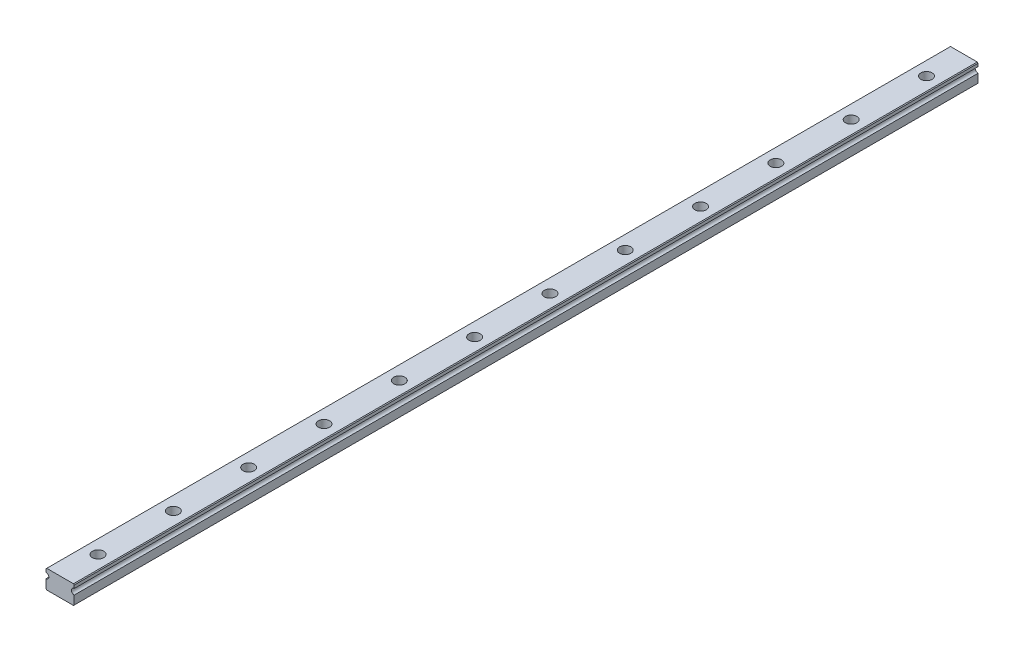
SolidWorks part; units mm, degrees
ref_plane "前视基准面" through (0, 0, 0) normal (0, 0, 1) x (1, 0, 0)
ref_plane "上视基准面" through (0, 0, 0) normal (0, 1, 0) x (1, 0, 0)
ref_plane "右视基准面" through (0, 0, 0) normal (1, 0, 0) x (0, 0, -1)
other "Configuration Table"
sketch "草图1" plane through (0, 0, 0) normal (0, 0, 1) x (1, 0, 0)
  line L0 (-7.6432, 0.2342) -> (-7.6432, -4.3658)
  line L1 (-7.6432, -4.3658) -> (-7.2432, -4.7658)
  line L2 (-7.2432, -4.7658) -> (6.9568, -4.7658)
  line L3 (6.9568, -4.7658) -> (7.3568, -4.3658)
  line L4 (7.3568, -4.3658) -> (7.3568, 0.2342)
  line L5 (7.3568, 3.2342) -> (7.3568, 4.8342)
  line L6 (7.3568, 4.8342) -> (6.9568, 5.2342)
  line L7 (6.9568, 5.2342) -> (-7.2432, 5.2342)
  line L8 (-7.2432, 5.2342) -> (-7.6432, 4.8342)
  line L9 (-7.6432, 4.8342) -> (-7.6432, 3.2342)
  arc A0 (5.8568, 1.7342) -> (7.3568, 0.2342) centre (7.3568, 1.7342) ccw
  arc A1 (7.3568, 3.2342) -> (5.8568, 1.7342) centre (7.3568, 1.7342) ccw
  arc A2 (-7.6432, 0.2342) -> (-7.6432, 3.2342) centre (-7.6432, 1.7342) ccw
extrude "凸台-拉伸1" add sketch "草图1" along normal blind 1000
sketch "草图2" plane through (0, 5.2342, 0) normal (0, 1, 0) x (1, 0, 0)
  line L0 (6.9568, 0) -> (-7.2432, 0) construction
  circle A0 centre (0, -20) radius 1.5
  dimension "D1" = 3
  dimension "D2" = 20
extrude "切除-拉伸1" cut sketch "草图2" against normal blind 20
sketch "草图3" plane through (0, 5.2342, 0) normal (0, 1, 0) x (1, 0, 0)
  circle A0 centre (0, -20) radius 3
  dimension "D1" = 6
extrude "切除-拉伸2" cut sketch "草图3" against normal blind 4.5
sketch "草图4" plane through (0, 5.2342, 0) normal (0, 1, 0) x (1, 0, 0)
  line L0 (0, 0) -> (0, -1341.5051) construction
pattern_linear "阵列(线性)1" count 25 spacing 40 along (0, 0, 1) of "切除-拉伸2", "切除-拉伸1"
sketch "草图5" plane through (0, 0, 1000) normal (0, 0, 1) x (1, 0, 0)
  line L10 (-7.6432, 0.2342) -> (-7.6432, -4.3658)
  line L11 (-7.6432, -4.3658) -> (-7.2432, -4.7658)
  line L12 (-7.2432, -4.7658) -> (6.9568, -4.7658)
  line L13 (6.9568, -4.7658) -> (7.3568, -4.3658)
  line L14 (7.3568, -4.3658) -> (7.3568, 0.2342)
  line L15 (7.3568, 3.2342) -> (7.3568, 4.8342)
  line L16 (7.3568, 4.8342) -> (6.9568, 5.2342)
  line L17 (6.9568, 5.2342) -> (-7.2432, 5.2342)
  line L18 (-7.2432, 5.2342) -> (-7.6432, 4.8342)
  line L19 (-7.6432, 4.8342) -> (-7.6432, 3.2342)
  line L20 (-7.6432, 0.2342) -> (-7.6432, -4.3658)
  line L21 (-7.6432, -4.3658) -> (-7.2432, -4.7658)
  line L22 (-7.2432, -4.7658) -> (6.9568, -4.7658)
  line L23 (6.9568, -4.7658) -> (7.3568, -4.3658)
  line L24 (7.3568, -4.3658) -> (7.3568, 0.2342)
  line L25 (7.3568, 3.2342) -> (7.3568, 4.8342)
  line L26 (7.3568, 4.8342) -> (6.9568, 5.2342)
  line L27 (6.9568, 5.2342) -> (-7.2432, 5.2342)
  line L28 (-7.2432, 5.2342) -> (-7.6432, 4.8342)
  line L29 (-7.6432, 4.8342) -> (-7.6432, 3.2342)
  arc A2 (-7.6432, 0.2342) -> (-7.6432, 3.2342) centre (-7.6432, 1.7342) ccw
  arc A3 (7.3568, 3.2342) -> (7.3568, 0.2342) centre (7.3568, 1.7342) ccw
  arc A4 (-7.6432, 0.2342) -> (-7.6432, 3.2342) centre (-7.6432, 1.7342) ccw
  arc A5 (7.3568, 3.2342) -> (7.3568, 0.2342) centre (7.3568, 1.7342) ccw
  dimension "D1" = 0
sketch "草图6" plane through (0, 0, 0) normal (0, 0, -1) x (-1, 0, 0)
  line L10 (7.6432, 3.2342) -> (7.6432, 4.8342)
  line L11 (7.6432, 4.8342) -> (7.2432, 5.2342)
  line L12 (7.2432, 5.2342) -> (-6.9568, 5.2342)
  line L13 (-6.9568, 5.2342) -> (-7.3568, 4.8342)
  line L14 (-7.3568, 4.8342) -> (-7.3568, 3.2342)
  line L15 (-7.3568, 0.2342) -> (-7.3568, -4.3658)
  line L16 (-7.3568, -4.3658) -> (-6.9568, -4.7658)
  line L17 (-6.9568, -4.7658) -> (7.2432, -4.7658)
  line L18 (7.2432, -4.7658) -> (7.6432, -4.3658)
  line L19 (7.6432, -4.3658) -> (7.6432, 0.2342)
  line L20 (7.6432, 3.2342) -> (7.6432, 4.8342)
  line L21 (7.6432, 4.8342) -> (7.2432, 5.2342)
  line L22 (7.2432, 5.2342) -> (-6.9568, 5.2342)
  line L23 (-6.9568, 5.2342) -> (-7.3568, 4.8342)
  line L24 (-7.3568, 4.8342) -> (-7.3568, 3.2342)
  line L25 (-7.3568, 0.2342) -> (-7.3568, -4.3658)
  line L26 (-7.3568, -4.3658) -> (-6.9568, -4.7658)
  line L27 (-6.9568, -4.7658) -> (7.2432, -4.7658)
  line L28 (7.2432, -4.7658) -> (7.6432, -4.3658)
  line L29 (7.6432, -4.3658) -> (7.6432, 0.2342)
  arc A2 (7.6432, 3.2342) -> (7.6432, 0.2342) centre (7.6432, 1.7342) ccw
  arc A3 (-7.3568, 0.2342) -> (-7.3568, 3.2342) centre (-7.3568, 1.7342) ccw
  arc A4 (7.6432, 3.2342) -> (7.6432, 0.2342) centre (7.6432, 1.7342) ccw
  arc A5 (-7.3568, 0.2342) -> (-7.3568, 3.2342) centre (-7.3568, 1.7342) ccw
  dimension "D1" = 0
extrude "切除-拉伸4" cut sketch "草图6" against normal blind 80
sketch "草图7" plane through (0, 0, 80) normal (0, 0, -1) x (-1, 0, 0)
  line L10 (7.6432, 3.2342) -> (7.6432, 4.8342)
  line L11 (7.6432, 4.8342) -> (7.2432, 5.2342)
  line L12 (7.2432, 5.2342) -> (-6.9568, 5.2342)
  line L13 (-6.9568, 5.2342) -> (-7.3568, 4.8342)
  line L14 (-7.3568, 4.8342) -> (-7.3568, 3.2342)
  line L15 (-7.3568, 0.2342) -> (-7.3568, -4.3658)
  line L16 (-7.3568, -4.3658) -> (-6.9568, -4.7658)
  line L17 (-6.9568, -4.7658) -> (7.2432, -4.7658)
  line L18 (7.2432, -4.7658) -> (7.6432, -4.3658)
  line L19 (7.6432, -4.3658) -> (7.6432, 0.2342)
  line L20 (7.6432, 3.2342) -> (7.6432, 4.8342)
  line L21 (7.6432, 4.8342) -> (7.2432, 5.2342)
  line L22 (7.2432, 5.2342) -> (-6.9568, 5.2342)
  line L23 (-6.9568, 5.2342) -> (-7.3568, 4.8342)
  line L24 (-7.3568, 4.8342) -> (-7.3568, 3.2342)
  line L25 (-7.3568, 0.2342) -> (-7.3568, -4.3658)
  line L26 (-7.3568, -4.3658) -> (-6.9568, -4.7658)
  line L27 (-6.9568, -4.7658) -> (7.2432, -4.7658)
  line L28 (7.2432, -4.7658) -> (7.6432, -4.3658)
  line L29 (7.6432, -4.3658) -> (7.6432, 0.2342)
  arc A2 (7.6432, 3.2342) -> (7.6432, 0.2342) centre (7.6432, 1.7342) ccw
  arc A3 (-7.3568, 0.2342) -> (-7.3568, 3.2342) centre (-7.3568, 1.7342) ccw
  arc A4 (7.6432, 3.2342) -> (7.6432, 0.2342) centre (7.6432, 1.7342) ccw
  arc A5 (-7.3568, 0.2342) -> (-7.3568, 3.2342) centre (-7.3568, 1.7342) ccw
  dimension "D1" = 0
extrude "切除-拉伸5" cut sketch "草图7" against normal blind 80
sketch "草图8" plane through (0, 0, 160) normal (0, 0, -1) x (-1, 0, 0)
  line L10 (7.6432, 3.2342) -> (7.6432, 4.8342)
  line L11 (7.6432, 4.8342) -> (7.2432, 5.2342)
  line L12 (7.2432, 5.2342) -> (-6.9568, 5.2342)
  line L13 (-6.9568, 5.2342) -> (-7.3568, 4.8342)
  line L14 (-7.3568, 4.8342) -> (-7.3568, 3.2342)
  line L15 (-7.3568, 0.2342) -> (-7.3568, -4.3658)
  line L16 (-7.3568, -4.3658) -> (-6.9568, -4.7658)
  line L17 (-6.9568, -4.7658) -> (7.2432, -4.7658)
  line L18 (7.2432, -4.7658) -> (7.6432, -4.3658)
  line L19 (7.6432, -4.3658) -> (7.6432, 0.2342)
  line L20 (7.6432, 3.2342) -> (7.6432, 4.8342)
  line L21 (7.6432, 4.8342) -> (7.2432, 5.2342)
  line L22 (7.2432, 5.2342) -> (-6.9568, 5.2342)
  line L23 (-6.9568, 5.2342) -> (-7.3568, 4.8342)
  line L24 (-7.3568, 4.8342) -> (-7.3568, 3.2342)
  line L25 (-7.3568, 0.2342) -> (-7.3568, -4.3658)
  line L26 (-7.3568, -4.3658) -> (-6.9568, -4.7658)
  line L27 (-6.9568, -4.7658) -> (7.2432, -4.7658)
  line L28 (7.2432, -4.7658) -> (7.6432, -4.3658)
  line L29 (7.6432, -4.3658) -> (7.6432, 0.2342)
  arc A2 (7.6432, 3.2342) -> (7.6432, 0.2342) centre (7.6432, 1.7342) ccw
  arc A3 (-7.3568, 0.2342) -> (-7.3568, 3.2342) centre (-7.3568, 1.7342) ccw
  arc A4 (7.6432, 3.2342) -> (7.6432, 0.2342) centre (7.6432, 1.7342) ccw
  arc A5 (-7.3568, 0.2342) -> (-7.3568, 3.2342) centre (-7.3568, 1.7342) ccw
  dimension "D1" = 0
extrude "切除-拉伸6" [suppressed] cut sketch "草图8" against normal blind 20
sketch "草图9" plane through (0, 0, 1000) normal (0, 0, 1) x (1, 0, 0)
  line L10 (-7.6432, 0.2342) -> (-7.6432, -4.3658)
  line L11 (-7.6432, -4.3658) -> (-7.2432, -4.7658)
  line L12 (-7.2432, -4.7658) -> (6.9568, -4.7658)
  line L13 (6.9568, -4.7658) -> (7.3568, -4.3658)
  line L14 (7.3568, -4.3658) -> (7.3568, 0.2342)
  line L15 (7.3568, 3.2342) -> (7.3568, 4.8342)
  line L16 (7.3568, 4.8342) -> (6.9568, 5.2342)
  line L17 (6.9568, 5.2342) -> (-7.2432, 5.2342)
  line L18 (-7.2432, 5.2342) -> (-7.6432, 4.8342)
  line L19 (-7.6432, 4.8342) -> (-7.6432, 3.2342)
  line L20 (-7.6432, 0.2342) -> (-7.6432, -4.3658)
  line L21 (-7.6432, -4.3658) -> (-7.2432, -4.7658)
  line L22 (-7.2432, -4.7658) -> (6.9568, -4.7658)
  line L23 (6.9568, -4.7658) -> (7.3568, -4.3658)
  line L24 (7.3568, -4.3658) -> (7.3568, 0.2342)
  line L25 (7.3568, 3.2342) -> (7.3568, 4.8342)
  line L26 (7.3568, 4.8342) -> (6.9568, 5.2342)
  line L27 (6.9568, 5.2342) -> (-7.2432, 5.2342)
  line L28 (-7.2432, 5.2342) -> (-7.6432, 4.8342)
  line L29 (-7.6432, 4.8342) -> (-7.6432, 3.2342)
  arc A2 (-7.6432, 0.2342) -> (-7.6432, 3.2342) centre (-7.6432, 1.7342) ccw
  arc A3 (7.3568, 3.2342) -> (7.3568, 0.2342) centre (7.3568, 1.7342) ccw
  arc A4 (-7.6432, 0.2342) -> (-7.6432, 3.2342) centre (-7.6432, 1.7342) ccw
  arc A5 (7.3568, 3.2342) -> (7.3568, 0.2342) centre (7.3568, 1.7342) ccw
  dimension "D1" = 0
extrude "切除-拉伸7" cut sketch "草图9" against normal blind 360
